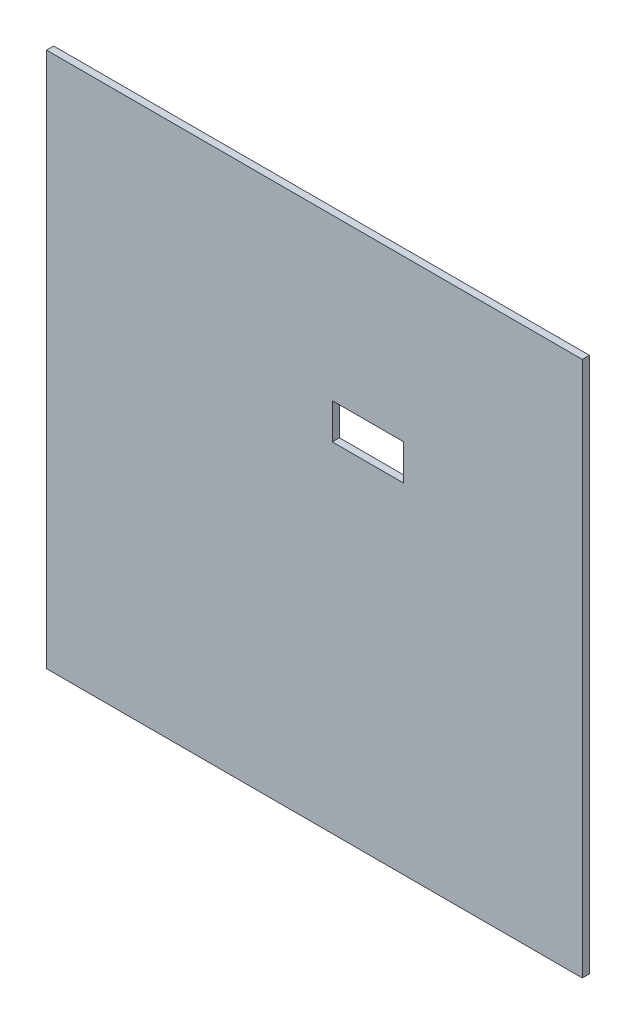
SolidWorks part; units mm, degrees
ref_plane "Front Plane" through (0, 0, 0) normal (0, 0, 1) x (1, 0, 0)
ref_plane "Top Plane" through (0, 0, 0) normal (0, 1, 0) x (1, 0, 0)
ref_plane "Right Plane" through (0, 0, 0) normal (1, 0, 0) x (0, 0, -1)
sketch "Sketch8" plane through (0, 0, 0) normal (0, 0, 1) x (1, 0, 0)
  line L1 (-5000, 5000) -> (10000, 5000)
  line L2 (-5000, 5000) -> (-5000, -10000)
  line L3 (-5000, -10000) -> (10000, -10000)
  line L4 (10000, 5000) -> (10000, -10000)
  dimension "D1" = 15000
  dimension "D2" = 15000
  dimension "D3" = 5000
  dimension "D4" = 5000
extrude "Boss-Extrude1" add sketch "Sketch8" along normal blind 200
sketch "Sketch9" plane through (0, 0, 200) normal (0, 0, 1) x (1, 0, 0)
  line L0 (-5000, 5000) -> (-5000, -10000) construction
  line L1 (3000, 500) -> (5000, 500)
  line L2 (3000, 500) -> (3000, -500)
  line L3 (3000, -500) -> (5000, -500)
  line L4 (5000, 500) -> (5000, -500)
  line L5 (10000, 5000) -> (-5000, 5000) construction
  point P6 (4000, 500)
  dimension "D1" = 2000
  dimension "D2" = 1000
  dimension "D3" = 8000
  dimension "D4" = 4500
extrude "Cut-Extrude3" cut sketch "Sketch9" against normal through all
